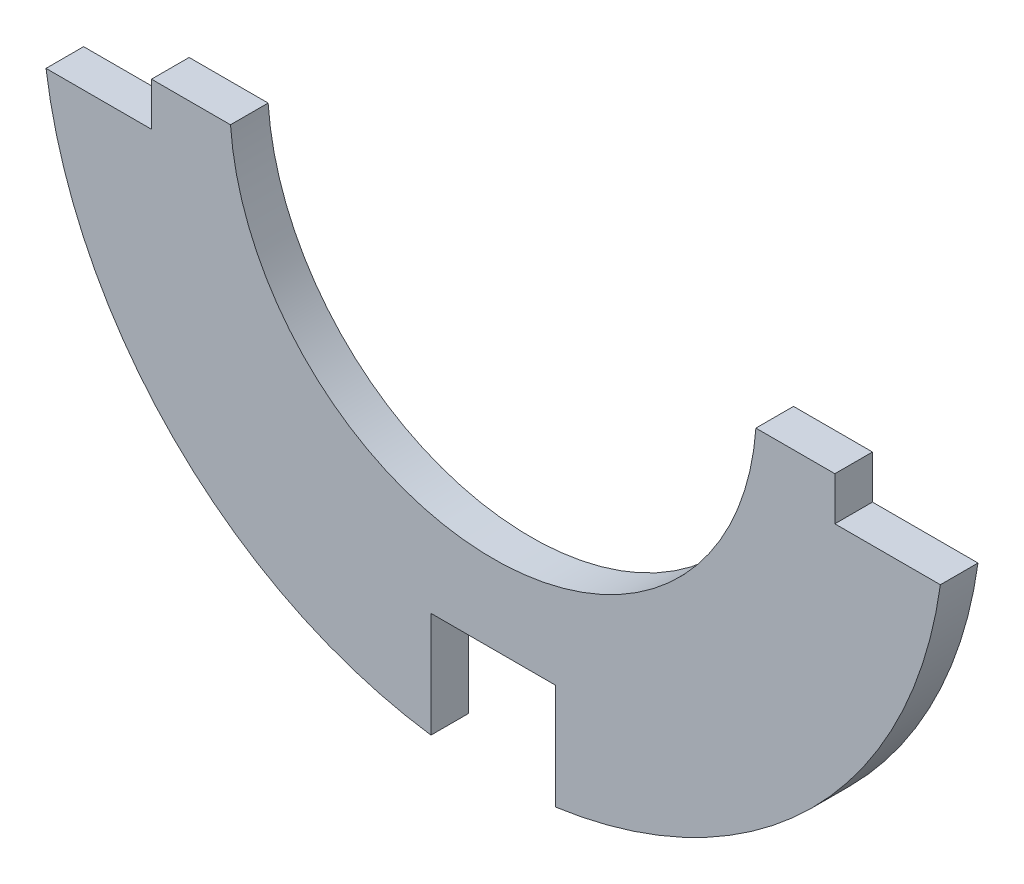
SolidWorks part; units mm, degrees
material "mdf"
ref_plane "Front Plane" through (0, 0, 0) normal (0, 0, 1) x (1, 0, 0)
ref_plane "Top Plane" through (0, 0, 0) normal (0, 1, 0) x (1, 0, 0)
ref_plane "Right Plane" through (0, 0, 0) normal (1, 0, 0) x (0, 0, -1)
sketch "Sketch1" plane through (0, 0, 0) normal (0, 0, 1) x (1, 0, 0)
  line L0 (0, 0) -> (-185.7744, -321.7707) construction
  line L5 (21, -150.9462) -> (21, -115.332)
  line L16 (150.9462, -21) -> (115.332, -21)
  line L17 (115.332, -21) -> (115.332, -6.35)
  line L24 (0, 0) -> (0, -371.5487) construction
  line L25 (0, -88.9) -> (0, -115.332)
  line L30 (115.332, -6.35) -> (88.6729, -6.35)
  line L34 (163.332, -21) -> (115.332, -21) construction
  line L37 (0, -6.35) -> (500, -6.35) construction
  line L38 (0, -115.332) -> (21, -115.332)
  arc A2 (21, -150.9462) -> (150.9462, -21) centre (0, 0) ccw
  arc A7 (0, -88.9) -> (88.6729, -6.35) centre (0, 0) ccw
  point P28 (0, 0)
  point P49 (0, 0)
  dimension "D1" = 152.4
  dimension "D2" = 88.9
  dimension "D5" = 14.65
extrude "Boss-Extrude4" add sketch "Sketch1" along normal mid plane 12.7 contours A2 L16 L17 L30 A7 L25 L38 L5
mirror "Mirror1" about plane through (0, 0, 0) normal (1, 0, 0) of "Boss-Extrude4"
